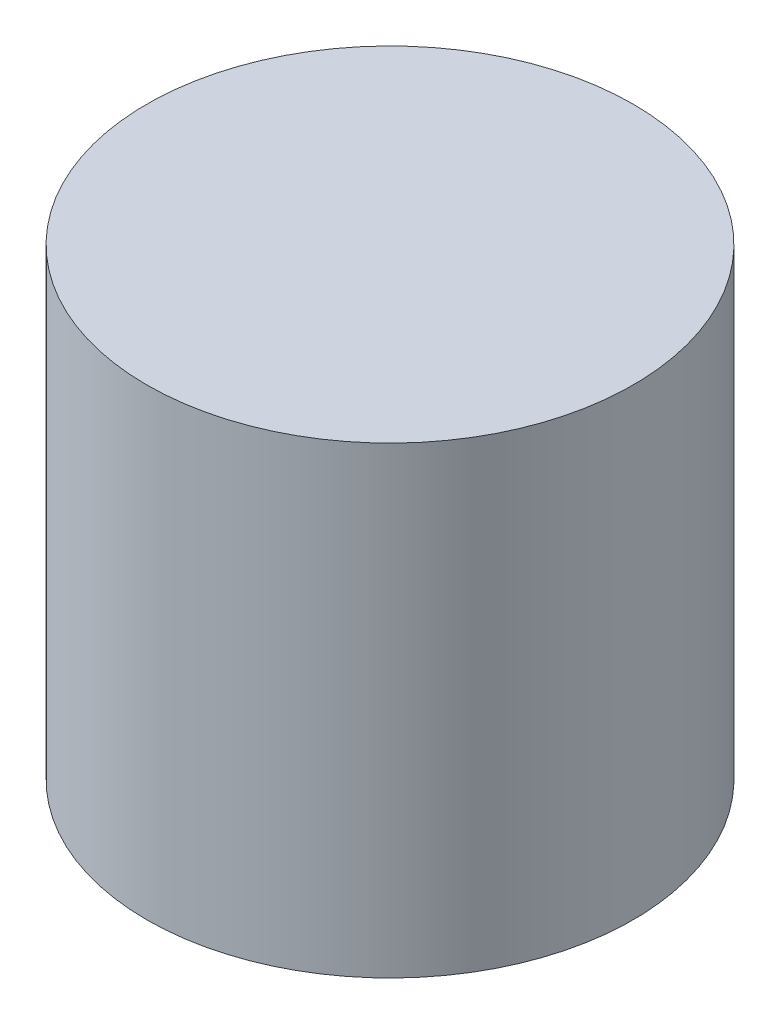
SolidWorks part; units mm, degrees
material "6061-T6 (SS)"
ref_plane "Alzado" through (0, 0, 0) normal (0, 0, 1) x (1, 0, 0)
ref_plane "Planta" through (0, 0, 0) normal (0, 1, 0) x (1, 0, 0)
ref_plane "Vista lateral" through (0, 0, 0) normal (1, 0, 0) x (0, 0, -1)
sketch "Croquis1" plane through (0, 0, 0) normal (0, 1, 0) x (1, 0, 0)
  circle A0 centre (0, 0) radius 3.15
  dimension "D1" = 6.3
extrude "Saliente-Extruir1" add sketch "Croquis1" along normal blind 6
